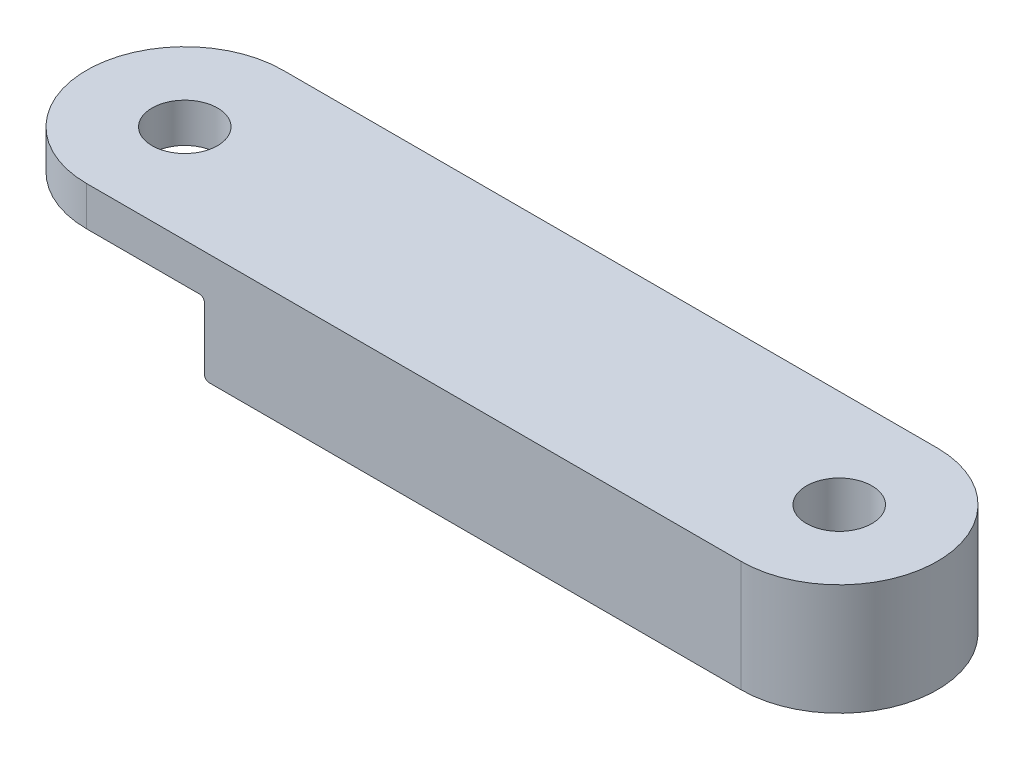
SolidWorks part; units mm, degrees
ref_plane "Front Plane" through (0, 0, 0) normal (0, 0, 1) x (1, 0, 0)
ref_plane "Top Plane" through (0, 0, 0) normal (0, 1, 0) x (1, 0, 0)
ref_plane "Right Plane" through (0, 0, 0) normal (1, 0, 0) x (0, 0, -1)
sketch "Sketch1" plane through (0, 0, 0) normal (0, 1, 0) x (1, 0, 0)
  line L0 (-50, 0) -> (0, 0) construction
  line L1 (-50, 7.5) -> (0, 7.5)
  line L2 (-50, -7.5) -> (0, -7.5)
  arc A0 (-50, 7.5) -> (-50, -7.5) centre (-50, 0) ccw
  arc A1 (0, -7.5) -> (0, 7.5) centre (0, 0) ccw
  circle A2 centre (-50, 0) radius 2.4
  circle A3 centre (0, 0) radius 2.4
  point P3 (-25, 0)
  dimension "D1" = 50
  dimension "D2" = 15
extrude "Boss-Extrude1" add sketch "Sketch1" along normal blind 15
sketch "Sketch2" plane through (0, 0, 0) normal (0, 1, 0) x (1, 0, 0)
  line L0 (-50, -7.5) -> (0, -7.5) construction
  line L1 (-50, 7.5) -> (-41, 7.5)
  line L3 (-50, -7.5) -> (-41, -7.5)
  line L4 (-41, 7.5) -> (-41, -7.5)
  circle A0 centre (-50, 0) radius 2.4
  arc A1 (-50, 7.5) -> (-50, -7.5) centre (-50, 0) ccw
  dimension "D1" = 9
extrude "Cut-Extrude1" cut sketch "Sketch2" along normal blind 12
sketch "Sketch3" plane through (0, 0, 0) normal (0, -1, 0) x (1, 0, 0)
  line L1 (-64.9891, 13.145) -> (16.7746, 13.145)
  line L2 (-64.9891, 13.145) -> (-64.9891, -13.145)
  line L3 (-64.9891, -13.145) -> (16.7746, -13.145)
  line L4 (16.7746, 13.145) -> (16.7746, -13.145)
extrude "Cut-Extrude2" cut sketch "Sketch3" against normal blind 5
scale "Scale1" scale about centroid uniform scaling yes scale factor 0.8
sketch "Sketch4" plane through (0, 14.0577, 0) normal (0, 1, 0) x (1, 0, 0)
  circle A0 centre (-44.0992, 0) radius 2
  circle A1 centre (-4.0992, 0) radius 2
extrude "Cut-Extrude3" cut sketch "Sketch4" against normal through all
sketch "Sketch5" plane through (0, 6.0577, 0) normal (0, -1, 0) x (1, 0, 0)
  line L1 (-38.9497, 8.8381) -> (3.0651, 8.8381)
  line L2 (-38.9497, 8.8381) -> (-38.9497, -10.273)
  line L3 (-38.9497, -10.273) -> (3.0651, -10.273)
  line L4 (3.0651, 8.8381) -> (3.0651, -10.273)
extrude "Cut-Extrude4" cut sketch "Sketch5" against normal blind 1.2
fillet "Fillet1" radius 0.3 1 edges at (-36.8992, 11.6577, 0)
fillet "Fillet3" radius 0.3 1 edges at (-36.8992, 7.2577, 0)
